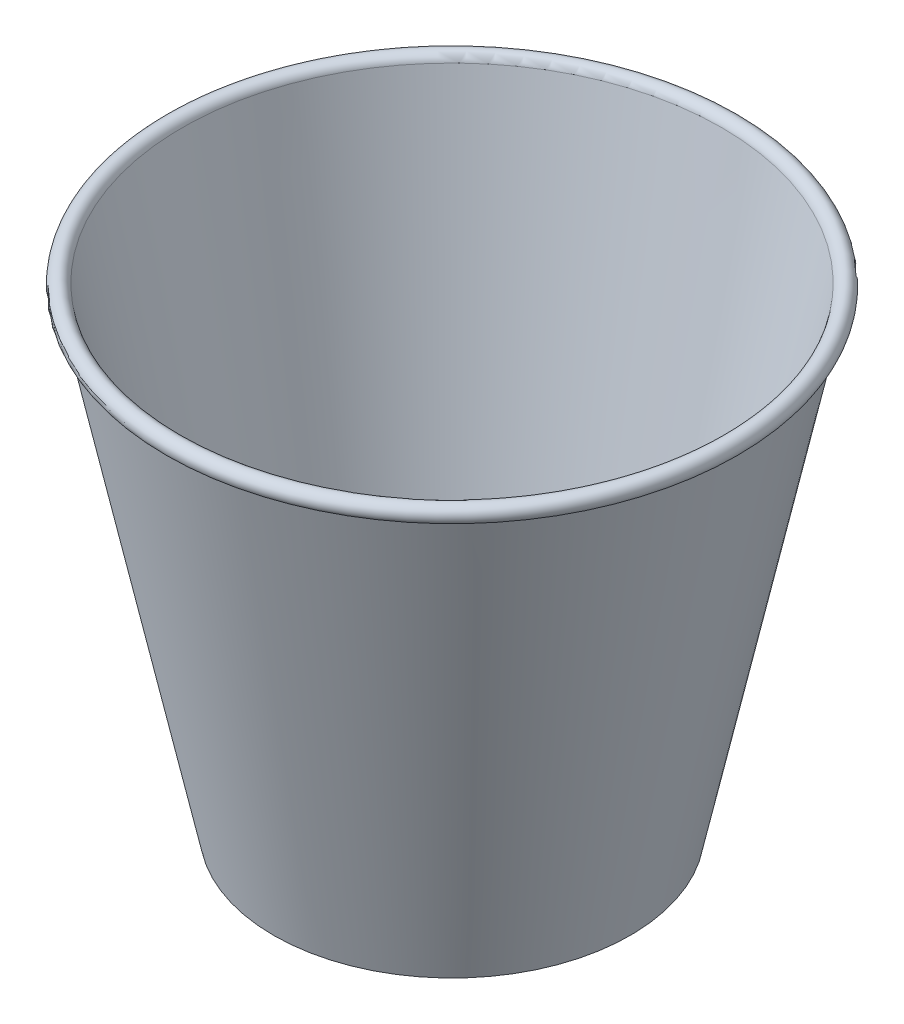
SolidWorks part; units mm, degrees
ref_plane "Front Plane" through (0, 0, 0) normal (0, 0, 1) x (1, 0, 0)
ref_plane "Top Plane" through (0, 0, 0) normal (0, 1, 0) x (1, 0, 0)
ref_plane "Right Plane" through (0, 0, 0) normal (1, 0, 0) x (0, 0, -1)
sketch "Sketch1" plane through (0, 0, 0) normal (1, 0, 0) x (0, 0, -1)
  line L0 (0, 0) -> (-34, 0) construction
  line L1 (-34, 0) -> (-21.6001, -58.4594)
  line L2 (-36, -0.8252) -> (-34.9346, -1.3773)
  line L3 (-34.9346, -1.3773) -> (-22.5, -60)
  line L4 (0, 0) -> (0, -105.6429) construction
  line L5 (0, -58) -> (23.861, -58) construction
  line L6 (0, -59.5) -> (25.7024, -59.5) construction
  line L7 (0, -58) -> (0, -59.5)
  arc A0 (-34, 0) -> (-36, -0.8252) centre (-35.0761, -0.2282) ccw
  arc A1 (-21.6001, -58.4594) -> (0, -58) centre (0, -566) cw
  arc A2 (-22.5, -60) -> (0, -59.5) centre (0, -566) cw
  point P8 (-22.5, -58.3565)
  point P13 (-35.0352, -1.323)
  dimension "D5" = 1.5
  dimension "D8" = 1.1
  dimension "D1" = 34
  dimension "D2" = 1.2
  dimension "D3" = 60
  dimension "D4" = 45
  dimension "D6" = 2
  dimension "D7" = 0.5
  dimension "D9" = 1.2
revolve "Revolve1" add sketch "Sketch1" angle 360 about L4
